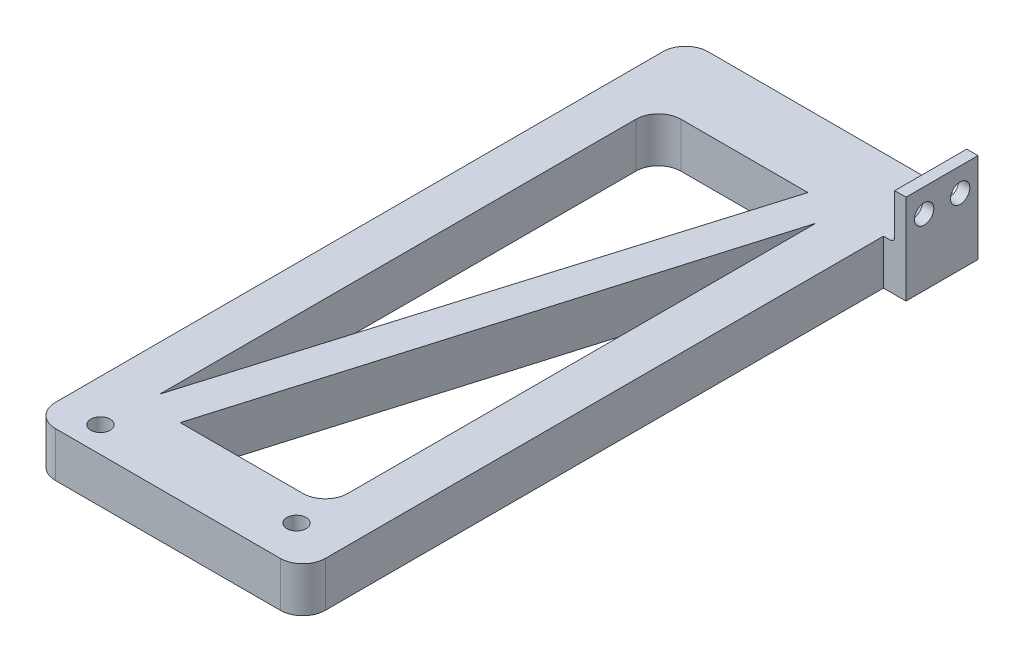
SolidWorks part; units mm, degrees
ref_plane "前视基准面" through (0, 0, 0) normal (0, 0, 1) x (1, 0, 0)
ref_plane "上视基准面" through (0, 0, 0) normal (0, 1, 0) x (1, 0, 0)
ref_plane "右视基准面" through (0, 0, 0) normal (1, 0, 0) x (0, 0, -1)
sketch "草图1" plane through (0, 0, 0) normal (0, 1, 0) x (1, 0, 0)
  line L0 (0.4312, 77.5722) -> (47.6808, 77.5722)
  line L1 (-17.3192, 77.5722) -> (0.4312, 77.5722)
  line L2 (-17.3192, 77.5722) -> (-17.3192, -67.4278)
  line L3 (-17.3192, -67.4278) -> (0.4312, -67.4278)
  line L7 (47.6808, 77.5722) -> (47.6808, 61.5722)
  line L12 (42.6808, -57.6007) -> (42.6808, -67.4278)
  line L13 (42.6808, -67.4278) -> (0.4312, -67.4278)
  line L15 (42.6808, -57.6007) -> (42.6808, 31.7573)
  line L17 (47.6808, 61.5722) -> (42.6808, 61.5722)
  line L18 (42.6808, 61.5722) -> (42.6808, 31.7573)
  line L19 (25.9063, 61.5722) -> (-7.3192, 61.5722)
  line L21 (0.4312, -52.4278) -> (32.6808, -52.4278)
  line L22 (32.6808, -52.4278) -> (32.6808, 56.5081)
  line L23 (-7.3192, 61.5722) -> (-7.3192, -49.2207)
  line L24 (25.9063, 61.5722) -> (-7.3192, -49.2207)
  line L25 (32.6808, 56.5081) -> (0.4312, -52.4278)
  point P0 (0, 0)
  dimension "D1" = 145
  dimension "D2" = 60
  dimension "D3" = 65
  dimension "D4" = 10
  dimension "D5" = 10
  dimension "D6" = 15
  dimension "D7" = 16
extrude "凸台-拉伸1" add sketch "草图1" along normal blind 10
sketch "草图4" plane through (0, 10, 0) normal (0, 1, 0) x (1, 0, 0)
  line L0 (45.1808, 77.5722) -> (45.1808, 61.5722)
  line L1 (47.6808, 77.5722) -> (-17.3192, 77.5722) construction
  line L2 (42.6808, 61.5722) -> (47.6808, 61.5722) construction
  line L3 (45.1808, 61.5722) -> (47.6808, 61.5722)
  line L4 (47.6808, 61.5722) -> (47.6808, 77.5722)
  line L5 (47.6808, 77.5722) -> (45.1808, 77.5722)
  dimension "D1" = 2.5
extrude "凸台-拉伸2" add sketch "草图4" along normal blind 10
sketch "草图5" plane through (45.1808, 0, 0) normal (-1, 0, 0) x (0, 0, 1)
  line L0 (-73.6076, 14.7525) -> (-60.8688, 14.7525) construction
  circle A0 centre (-73.6076, 14.7525) radius 2.15
  circle A1 centre (-65.6076, 14.7525) radius 2.15
  dimension "D2" = 4.3
  dimension "D3" = 4.3
  dimension "D1" = 8
extrude "切除-拉伸1" cut sketch "草图5" against normal up to next
sketch "草图6" plane through (0, 10, 0) normal (0, 1, 0) x (1, 0, 0)
  line L0 (32.8487, -73.9107) -> (32.6808, -58.8401) construction
  line L1 (32.6808, -52.4278) -> (32.6808, 56.5081) construction
  line L2 (-25.0369, -58.8401) -> (44.4062, -58.8401) construction
  circle A0 centre (-8.0192, -61.6901) radius 2.15
  circle A1 centre (32.6808, -58.8401) radius 2.15
  dimension "D1" = 4.3
  dimension "D2" = 4.3
  dimension "D3" = 40.7
  dimension "D4" = 2.85
extrude "切除-拉伸2" cut sketch "草图6" against normal up to next
fillet "圆角1" radius 5 3 edges at (-17.3192, 5, -77.5722) (42.6808, 5, 67.4278) (-17.3192, 5, 67.4278)
fillet "圆角2" radius 5 2 edges at (32.6808, 5, 52.4278) (-7.3192, 5, -61.5722)
fillet "圆角3" radius 1 1 edges at (45.1808, 10, -69.5722)
